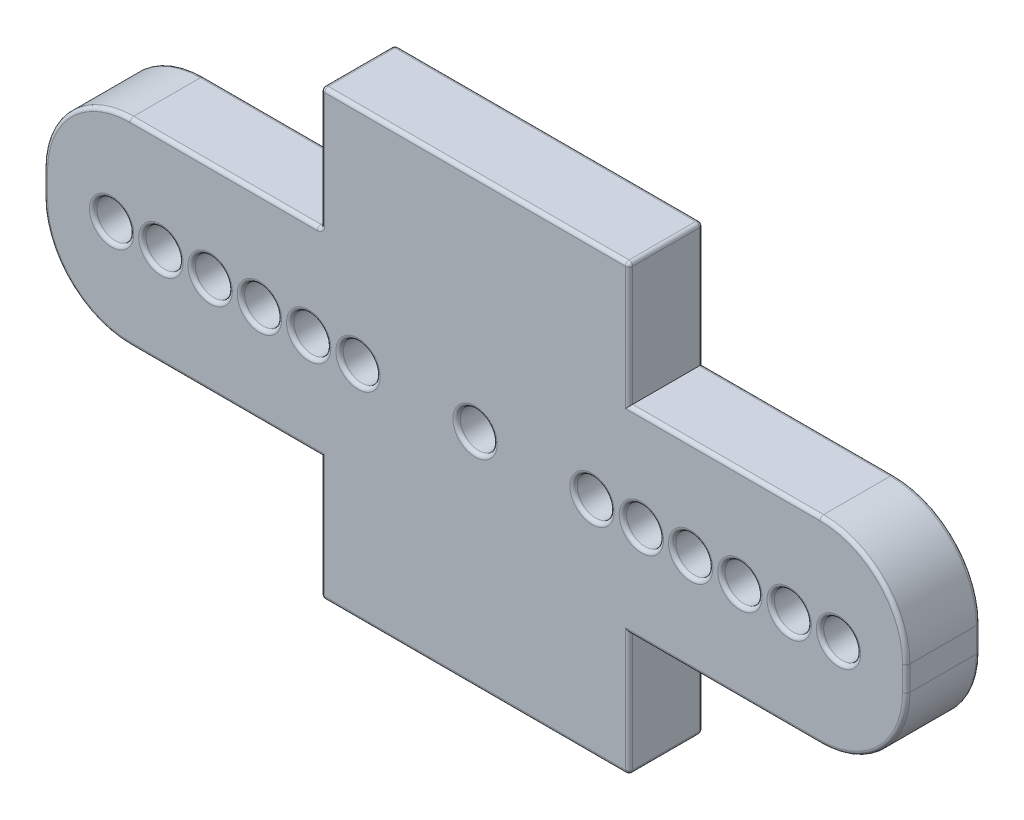
SolidWorks part; units mm, degrees
material "AISI 1020"
ref_plane "Front Plane" through (0, 0, 0) normal (0, 0, 1) x (1, 0, 0)
ref_plane "Top Plane" through (0, 0, 0) normal (0, 1, 0) x (1, 0, 0)
ref_plane "Right Plane" through (0, 0, 0) normal (1, 0, 0) x (0, 0, -1)
sketch "Sketch1" plane through (0, 0, 0) normal (0, 0, 1) x (1, 0, 0)
  line L0 (-17.5, 0.5) -> (-17.5, -0.5)
  line L1 (6.25, -9) -> (-6.25, -9) construction
  line L2 (6.25, -9) -> (6.25, 9) construction
  line L3 (6.25, 9) -> (-6.25, 9) construction
  line L4 (-6.25, -9) -> (-6.25, 9) construction
  line L5 (6.25, -9) -> (-6.25, 9) construction
  line L6 (6.25, 9) -> (-6.25, -9) construction
  line L7 (17.5, -4) -> (-17.5, -4) construction
  line L8 (17.5, -4) -> (17.5, 4) construction
  line L9 (17.5, 4) -> (-17.5, 4) construction
  line L10 (-17.5, -4) -> (-17.5, 4) construction
  line L11 (17.5, -4) -> (-17.5, 4) construction
  line L12 (17.5, 4) -> (-17.5, -4) construction
  line L13 (-14, -4) -> (-6.25, -4)
  line L14 (-6.25, -4) -> (-6.25, -9)
  line L15 (-6.25, -9) -> (6.25, -9)
  line L16 (6.25, -9) -> (6.25, -4)
  line L17 (6.25, -4) -> (14, -4)
  line L18 (17.5, -0.5) -> (17.5, 0.5)
  line L19 (14, 4) -> (6.25, 4)
  line L20 (6.25, 4) -> (6.25, 9)
  line L21 (6.25, 9) -> (-6.25, 9)
  line L22 (-6.25, 9) -> (-6.25, 4)
  line L23 (-6.25, 4) -> (-14, 4)
  circle A0 centre (0, 0) radius 0.75
  arc A1 (-14, 4) -> (-17.5, 0.5) centre (-14, 0.5) ccw
  arc A2 (-17.5, -0.5) -> (-14, -4) centre (-14, -0.5) ccw
  arc A3 (14, -4) -> (17.5, -0.5) centre (14, -0.5) ccw
  arc A4 (17.5, 0.5) -> (14, 4) centre (14, 0.5) ccw
  point P0 (0, 0)
  point P6 (0, 0)
  dimension "D5" = 1.5
  dimension "D6" = 3.5
  dimension "D1" = 8
  dimension "D2" = 35
  dimension "D3" = 12.5
  dimension "D4" = 18
extrude "Boss-Extrude2" add sketch "Sketch1" along normal mid plane 3
sketch "Sketch2" plane through (0, 0, 1.5) normal (0, 0, 1) x (1, 0, 0)
  line L0 (-17.5, 0) -> (17.5, 0) construction
  line L1 (-17.5, 0.5) -> (-17.5, -0.5) construction
  line L2 (17.5, -0.5) -> (17.5, 0.5) construction
  line L5 (6.25, -9) -> (6.25, -4) construction
  line L6 (-6.25, -9) -> (6.25, -9) construction
  circle A0 centre (-14.75, 0) radius 0.75
  circle A1 centre (-12.75, 0) radius 0.75
  circle A2 centre (-10.75, 0) radius 0.75
  circle A3 centre (-8.75, 0) radius 0.75
  circle A4 centre (-6.75, 0) radius 0.75
  circle A5 centre (-4.75, 0) radius 0.75
  point P7 (-4.75, 0)
  point P8 (-6.75, 0)
  point P9 (-8.75, 0)
  point P10 (-10.75, 0)
  point P11 (-12.75, 0)
  point P12 (-14.75, 0)
  dimension "D8" = 1.5
  dimension "D1" = 4.75
  dimension "D2" = 2.75
  dimension "D7" = 6
extrude "Cut-Extrude1" cut sketch "Sketch2" against normal up to next
mirror "Mirror1" about plane through (0, 0, 0) normal (1, 0, 0) of "Cut-Extrude1"
fillet "Fillet2" radius 0.15 63 edges at (4, 0, 1.5) (5.5, 0, -1.5) (6, 0, 1.5) (7.5, 0, -1.5) (8, 0, 1.5) (9.5, 0, -1.5) (10, 0, 1.5) (11.5, 0, -1.5) (12, 0, 1.5) (13.5, 0, -1.5) (14, 0, 1.5) (15.5, 0, -1.5) (-4, 0, -1.5) (-4, 0, 1.5) (-6, 0, -1.5) (-6, 0, 1.5) (-8, 0, -1.5) (-8, 0, 1.5) (-10, 0, -1.5) (-10, 0, 1.5) (-12, 0, -1.5) (-12, 0, 1.5) (-14, 0, -1.5) (-14, 0, 1.5) (0.75, 0, -1.5) (0.75, 0, 1.5) (-6.25, 6.5, -1.5) (-10.125, 4, -1.5) (-17.5, 0, -1.5) (-10.125, -4, -1.5) (-6.25, -6.5, -1.5) (0, -9, -1.5) (6.25, -6.5, -1.5) (10.125, -4, -1.5) (17.5, 0, -1.5) (10.125, 4, -1.5) (6.25, 6.5, -1.5) (0, 9, -1.5) (-10.125, 4, 1.5) (-17.5, 0, 1.5) (-10.125, -4, 1.5) (-6.25, -6.5, 1.5) (0, -9, 1.5) (6.25, -6.5, 1.5) (10.125, -4, 1.5) (17.5, 0, 1.5) (10.125, 4, 1.5) (6.25, 6.5, 1.5) (0, 9, 1.5) (-6.25, 9, 0) (6.25, 9, 0) (6.25, -9, 0) (-6.25, -9, 0) (-6.25, 6.5, 1.5) (-6.25, 4, 0) (-16.4749, 2.9749, -1.5) (-16.4749, -2.9749, -1.5) (16.4749, -2.9749, -1.5) (16.4749, 2.9749, -1.5) (-16.4749, 2.9749, 1.5) (-16.4749, -2.9749, 1.5) (16.4749, -2.9749, 1.5) (16.4749, 2.9749, 1.5)
